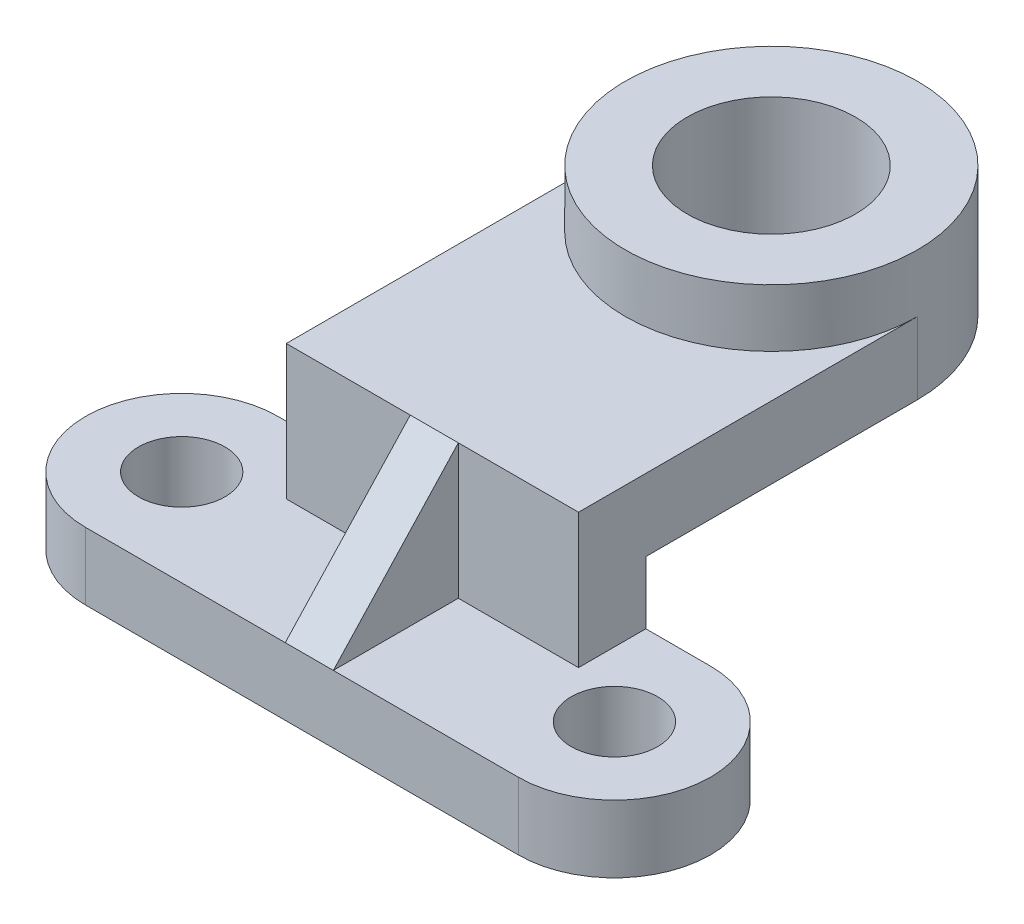
SolidWorks part; units mm, degrees
ref_plane "정면" through (0, 0, 0) normal (0, 0, 1) x (1, 0, 0)
ref_plane "윗면" through (0, 0, 0) normal (0, 1, 0) x (1, 0, 0)
ref_plane "우측면" through (0, 0, 0) normal (1, 0, 0) x (0, 0, -1)
sketch "스케치1" plane through (0, 0, 0) normal (0, 1, 0) x (1, 0, 0)
  line L0 (-48.7321, -74.9807) -> (131.2679, -74.9807) construction
  line L1 (-48.7321, -34.9807) -> (131.2679, -34.9807)
  line L2 (-48.7321, -114.9807) -> (131.2679, -114.9807)
  arc A0 (-48.7321, -34.9807) -> (-48.7321, -114.9807) centre (-48.7321, -74.9807) ccw
  arc A1 (131.2679, -114.9807) -> (131.2679, -34.9807) centre (131.2679, -74.9807) ccw
  circle A2 centre (-48.7321, -74.9807) radius 18
  circle A3 centre (131.2679, -74.9807) radius 18
  point P2 (41.2679, -74.9807)
  dimension "D1" = 36
  dimension "D2" = 40
  dimension "D3" = 180
extrude "보스-돌출1" add sketch "스케치1" along normal blind 28
sketch "스케치2" plane through (0, 28, 0) normal (0, 1, 0) x (1, 0, 0)
  line L0 (-17.2412, -62.9807) -> (-17.2412, 78.0193)
  line L1 (-17.2412, 78.0193) -> (104.3362, 78.0193)
  line L2 (104.3362, 78.0193) -> (104.3362, -62.9807)
  line L3 (104.3362, -62.9807) -> (-17.2412, -62.9807)
  line L4 (131.2679, -34.9807) -> (-48.7321, -34.9807) construction
  dimension "D1" = 28
  dimension "D2" = 141
extrude "보스-돌출2" add sketch "스케치2" along normal blind 56
sketch "스케치5" plane through (104.3362, 0, 0) normal (1, 0, 0) x (0, 0, -1)
  line L0 (78.0193, 84) -> (78.0193, 28) construction
  line L1 (-34.9807, 28) -> (78.0193, 28)
  line L2 (-34.9807, 28) -> (-34.9807, 54)
  line L3 (-34.9807, 54) -> (78.0193, 54)
  line L4 (78.0193, 28) -> (78.0193, 54)
  dimension "D1" = 26
extrude "컷-돌출1" cut sketch "스케치5" against normal blind 180
sketch "스케치7" plane through (0, 54, 0) normal (0, -1, 0) x (1, 0, 0)
  line L0 (-17.2412, -78.0193) -> (104.3362, -78.0193) construction
  line L1 (-17.2412, -78.0193) -> (-17.2412, 34.9807) construction
  line L2 (104.3362, -78.0193) -> (104.3362, 34.9807) construction
  circle A0 centre (43.5475, -78.0193) radius 35
  circle A1 centre (43.5475, -78.0193) radius 60.7887
  dimension "D1" = 70
extrude "보스-돌출4" add sketch "스케치7" against normal blind 54
sketch "스케치8" plane through (104.3362, 0, 0) normal (1, 0, 0) x (0, 0, -1)
  line L0 (-114.9807, 28) -> (-62.9807, 84)
  line L1 (-114.9807, 28) -> (-62.9807, 28)
  line L2 (-62.9807, 28) -> (-62.9807, 84)
extrude "보스-돌출5" add sketch "스케치8" along normal blind 20 from offset 70 contours L0 L2 L1 offset against normal yes
sketch "스케치9" plane through (0, 84, 0) normal (0, 1, 0) x (1, 0, 0)
  line L0 (78.5475, 78.0193) -> (8.5475, 78.0193) construction
  circle A0 centre (43.5475, 78.0193) radius 35
  dimension "D1" = 70
extrude "컷-돌출2" cut sketch "스케치9" against normal blind 20
sketch "스케치11" plane through (0, 84, 0) normal (0, 1, 0) x (1, 0, 0)
  line L0 (78.5475, 78.0193) -> (8.5475, 78.0193)
  arc A0 (8.5475, 78.0193) -> (78.5475, 78.0193) centre (43.5475, 78.0193) ccw
extrude "컷-돌출5" cut sketch "스케치11" against normal through all
